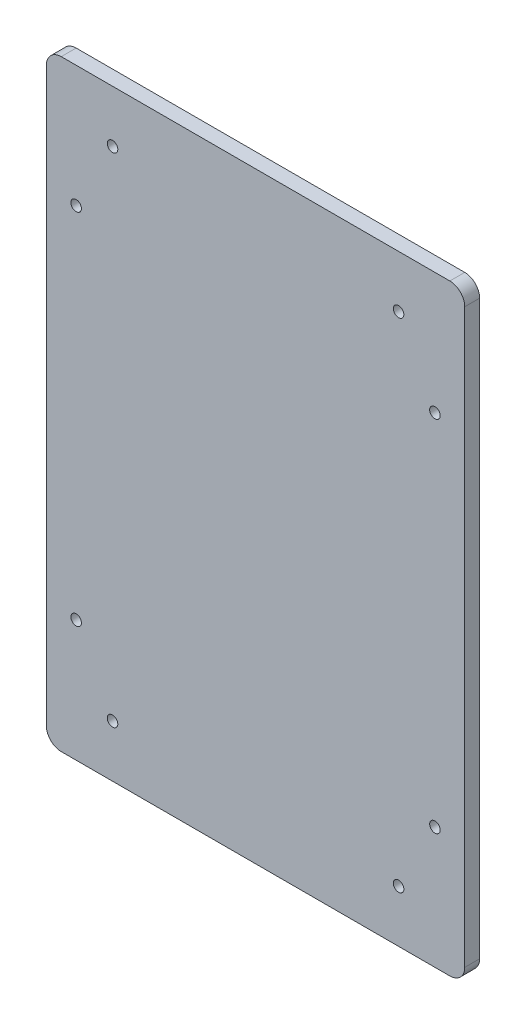
SolidWorks part; units mm, degrees
material "Acrylic (Medium-high impact)"
ref_plane "Front Plane" through (0, 0, 0) normal (0, 0, 1) x (1, 0, 0)
ref_plane "Top Plane" through (0, 0, 0) normal (0, 1, 0) x (1, 0, 0)
ref_plane "Right Plane" through (0, 0, 0) normal (1, 0, 0) x (0, 0, -1)
sketch "Sketch1" plane through (0, 0, 0) normal (0, 0, 1) x (1, 0, 0)
  line L0 (-62.6996, 115.57) -> (62.6996, 115.57) construction
  line L1 (76.4604, -76.4603) -> (-76.4603, -76.4604) construction
  line L2 (76.4604, -76.4603) -> (76.4604, 76.4603) construction
  line L3 (76.4604, 76.4603) -> (-76.4603, 76.4603) construction
  line L4 (-76.4603, -76.4604) -> (-76.4603, 76.4603) construction
  line L5 (76.4604, -76.4603) -> (-76.4603, 76.4603) construction
  line L6 (76.4604, 76.4603) -> (-76.4603, -76.4604) construction
  line L7 (-89.1603, -128.27) -> (89.1604, -128.27)
  line L8 (-89.1603, -128.27) -> (-89.1603, 128.27)
  line L9 (-89.1603, 128.27) -> (89.1604, 128.27)
  line L10 (89.1604, -128.27) -> (89.1604, 128.27)
  line L11 (-89.1603, -128.27) -> (89.1604, 128.27) construction
  line L12 (-89.1603, 128.27) -> (89.1604, -128.27) construction
  point P0 (0, 0)
  point P6 (0, 0)
  dimension "D1" = 152.9207
  dimension "D2" = 152.9207
  dimension "D3" = 12.7
  dimension "D4" = 12.7
extrude "Boss-Extrude1" add sketch "Sketch1" along normal blind 6.35
fillet "Fillet1" radius 6.35 4 edges at (89.1604, 128.27, 3.175) (89.1604, -128.27, 3.175) (-89.1603, -128.27, 3.175) (-89.1603, 128.27, 3.175)
hole_wizard "#8 Clearance Hole1" positions "Sketch3" profile "Sketch2" hole size "#8" standard "ANSI Inch" end condition through all
sketch "Sketch3" plane through (0, 0, 0) normal (0, 0, -1) x (-1, 0, 0)
  point P0 (-60.96, 106.045)
  point P3 (60.96, 106.045)
  point P6 (-60.96, -106.045)
  point P9 (60.96, -106.045)
  point P14 (-76.4604, -76.4603)
  point P17 (-76.4604, 76.4603)
  point P20 (76.4603, 76.4603)
  point P23 (76.4603, -76.4604)
sketch "Sketch2" plane through (60.96, 106.045, 0) normal (1, 0, 0) x (0, 1, 0)
  line L0 (0, 0) -> (0, 6.35)
  line L1 (0, 6.35) -> (2.2479, 6.35)
  line L2 (2.2479, 6.35) -> (2.2479, 0)
  line L5 (2.2479, 0) -> (0, 0)
  line L11 (0, -6.35) -> (0, 107.95) construction
  dimension "Thru Hole Dia." = 4.4958
  dimension "Thru Hole Depth" = 6.35
